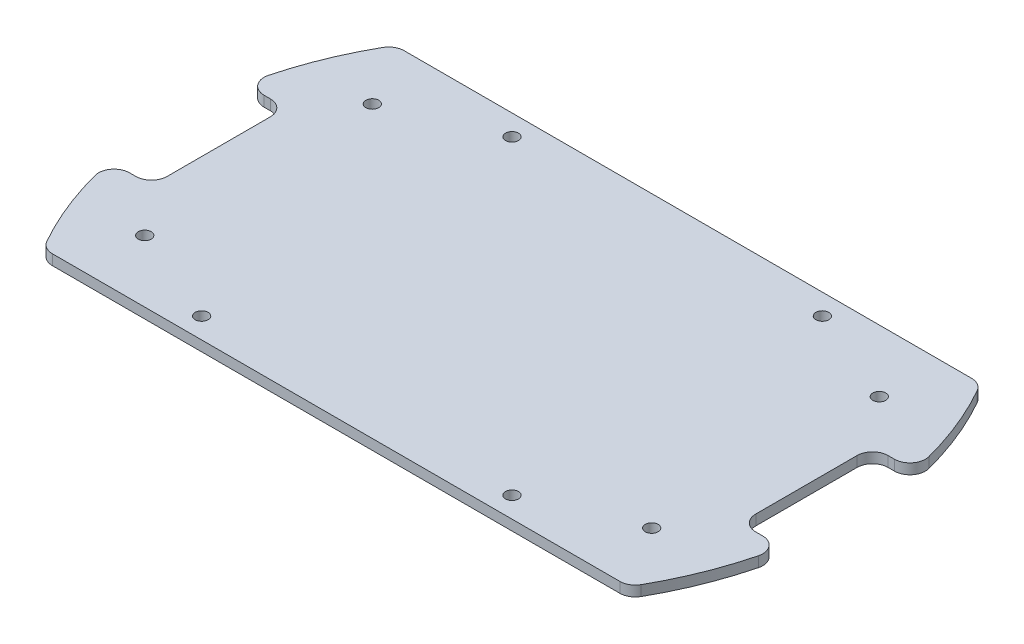
SolidWorks part; units mm, degrees
ref_plane "前基準面" through (0, 0, 0) normal (0, 0, 1) x (1, 0, 0)
ref_plane "上基準面" through (0, 0, 0) normal (0, 1, 0) x (1, 0, 0)
ref_plane "右基準面" through (0, 0, 0) normal (1, 0, 0) x (0, 0, -1)
sketch "草圖7" plane through (0, 0, 0) normal (0, 1, 0) x (1, 0, 0)
  line L1 (-34, 34) -> (34, 34)
  line L2 (-34, 34) -> (-34, -34)
  line L3 (-34, -34) -> (34, -34)
  line L4 (34, 34) -> (34, -34)
  line L5 (-34, 34) -> (34, -34) construction
  line L6 (-34, -34) -> (34, 34) construction
  point P0 (0, 0)
  point P7 (-30, 30)
  point P10 (30, 30)
  point P11 (30, -30)
  point P12 (-30, -30)
  point P13 (0, 0)
  dimension "D1" = 68
  dimension "D2" = 4
  dimension "D3" = 4
sketch "草圖10" plane through (0, 0, 0) normal (0, 1, 0) x (1, 0, 0)
  line L0 (-56.5685, 34) -> (56.5685, 34)
  line L1 (-34, 34) -> (34, 34) construction
  line L2 (-56.5685, -34) -> (56.5685, -34)
  line L3 (-34, -34) -> (34, -34) construction
  line L4 (-34, 34) -> (-34, -34) construction
  line L5 (0, 0) -> (0, 19.0172) construction
  line L6 (0, 0) -> (-12.2861, 0) construction
  line L7 (-56.707, 13) -> (-56.707, -13)
  line L8 (-64.707, 13) -> (64.707, 13)
  line L9 (56.707, 13) -> (56.707, -13)
  line L10 (-64.707, -13) -> (64.7924, -12.5675)
  arc A0 (-64.707, -13) -> (-56.5685, -34) centre (0, 0) ccw
  arc A3 (-56.5685, 34) -> (-64.707, 13) centre (0, 0) ccw
  arc A4 (64.707, 13) -> (56.5685, 34) centre (0, 0) ccw
  arc A5 (56.5685, -34) -> (64.7924, -12.5675) centre (0, 0) ccw
  point P12 (-49, 22)
  point P24 (56.707, 0)
  point P27 (-56.707, 0)
  dimension "D1" = 8
  dimension "D2" = 13
  dimension "D4" = 15
  dimension "D5" = 12
extrude "填料-伸長2" add sketch "草圖10" along normal blind 2
hole_wizard "M3x0.5  螺絲攻的螺孔鑽1" positions "3D草圖2" profile "草圖13" hole size "M3x0.5" standard "JIS"
sketch3d "3D草圖2"
  point P0 (-30, 0, -30)
  point P3 (-30, 2, -30)
  point P5 (-30, 2, 30)
  point P11 (30, 2, -30)
  point P13 (30, 2, 30)
sketch "草圖13" plane through (30, 2, 30) normal (1, 0, 0) x (0, 0, 1)
  line L0 (0, 0) -> (0, 4.7511)
  line L1 (0, 4.7511) -> (1.25, 4)
  line L2 (1.25, 4) -> (1.25, 0)
  line L5 (1.25, 0) -> (0, 0)
  line L10 (0, 4.7511) -> (-1.25, 4) construction
  line L11 (0, -6.35) -> (0, 107.95) construction
  dimension "鑽孔直徑" = 2.5
  dimension "鑽孔深度" = 4
  dimension "導頭角度" = 118
hole_wizard "M3x0.5  螺絲攻的螺孔鑽2" positions "3D草圖3" profile "草圖14" hole size "M3x0.5" standard "JIS"
sketch3d "3D草圖3"
  point P0 (-49, 2, -22)
sketch "草圖14" plane through (-49, 2, -22) normal (1, 0, 0) x (0, 0, 1)
  line L0 (0, 0) -> (0, 4.7511)
  line L1 (0, 4.7511) -> (1.25, 4)
  line L2 (1.25, 4) -> (1.25, 0)
  line L5 (1.25, 0) -> (0, 0)
  line L10 (0, 4.7511) -> (-1.25, 4) construction
  line L11 (0, -6.35) -> (0, 107.95) construction
  dimension "鑽孔直徑" = 2.5
  dimension "鑽孔深度" = 4
  dimension "導頭角度" = 118
pattern_linear "直線複製排列1" count 2 spacing 98 along (1, 0, 0) count 2 spacing 44 along (0, 0, 1) of "M3x0.5  螺絲攻的螺孔鑽2"
fillet "圓角4" radius 3 12 edges at (-56.5685, 1, -34) (56.5685, 1, -34) (64.707, 1, -13) (56.707, 1, -13) (56.707, 1, 12.5945) (64.7924, 1, 12.5675) (56.5685, 1, 34) (-56.707, 1, 12.9733) (-56.707, 1, -13) (-64.707, 1, -13) (-56.5685, 1, 34) (-64.707, 1, 13)
